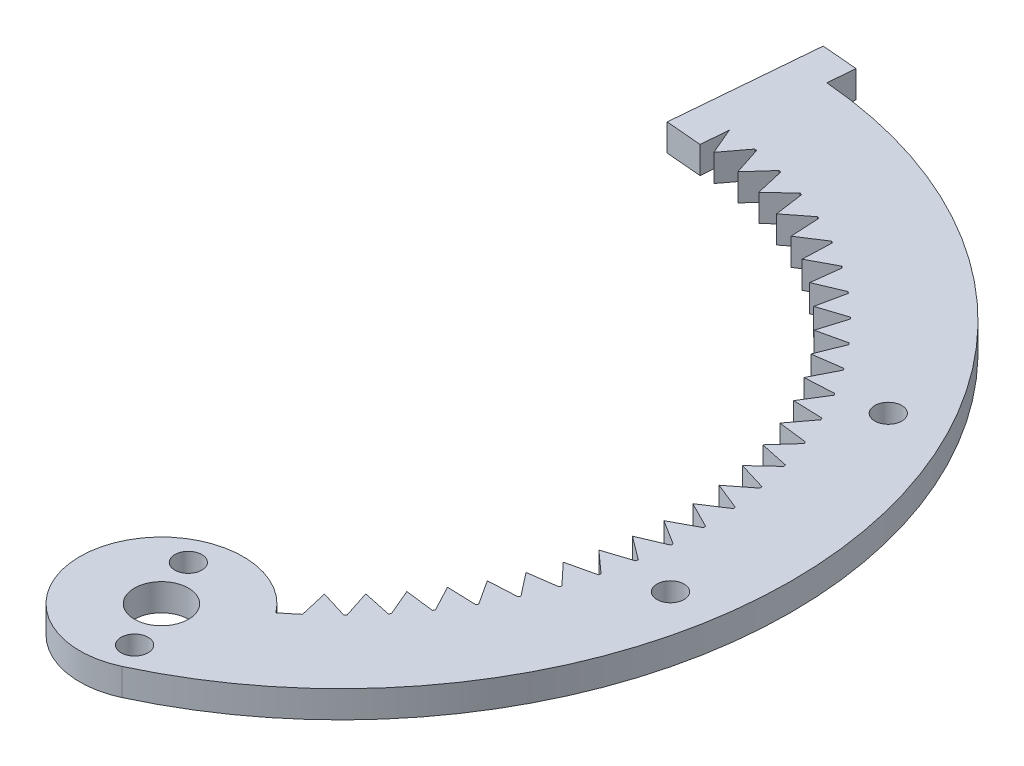
SolidWorks part; units mm, degrees
ref_plane "前视基准面" through (0, 0, 0) normal (0, 0, 1) x (1, 0, 0)
ref_plane "上视基准面" through (0, 0, 0) normal (0, 1, 0) x (1, 0, 0)
ref_plane "右视基准面" through (0, 0, 0) normal (1, 0, 0) x (0, 0, -1)
sketch "草图1" plane through (0, 0, 0) normal (0, 1, 0) x (1, 0, 0)
  line L0 (-22.706, 22.2911) -> (-15.0307, 111.7093) construction
  line L1 (-1.2848, 20.4524) -> (-44.7839, 24.1861) construction
  line L54 (-14.2519, 74.0104) -> (-13.9954, 76.9994)
  line L55 (-14.2519, 74.0104) -> (-18.2373, 74.3525)
  line L56 (-18.2373, 74.3525) -> (-16.8689, 90.2939)
  line L57 (-16.8689, 90.2939) -> (-12.8836, 89.9518)
  line L58 (-17.5531, 82.3232) -> (-4.3646, 81.1911) construction
  line L59 (-13.9954, 76.9994) -> (-12.7263, 74.0133)
  line L60 (-12.7263, 74.0133) -> (-10.7748, 76.6054)
  line L62 (-9.529, 73.4797) -> (-7.359, 75.8918)
  line L63 (-10.533, 76.565) -> (-9.529, 73.4797)
  line L64 (-6.3903, 72.6694) -> (-4.0184, 74.8833)
  line L65 (-7.1216, 75.8305) -> (-6.3903, 72.6694)
  line L66 (-3.3342, 71.5887) -> (-0.7783, 73.5874)
  line L67 (-3.7872, 74.8015) -> (-3.3342, 71.5887)
  line L68 (-0.384, 70.2458) -> (2.3364, 72.0141)
  line L69 (-0.5552, 73.4858) -> (-0.384, 70.2458)
  line L70 (2.438, 68.6508) -> (5.3022, 70.1753)
  line L71 (2.5499, 71.8935) -> (2.438, 68.6508)
  line L72 (5.1103, 66.816) -> (8.0964, 68.085)
  line L73 (5.5043, 70.0365) -> (5.1103, 66.816)
  line L74 (7.6125, 64.7552) -> (10.6978, 65.7592)
  line L75 (8.2857, 67.9292) -> (7.6125, 64.7552)
  line L76 (9.9255, 62.4842) -> (13.0866, 63.2154)
  line L77 (10.8728, 65.5874) -> (9.9255, 62.4842)
  line L78 (12.0318, 60.0202) -> (15.2446, 60.4732)
  line L79 (13.2459, 63.0291) -> (12.0318, 60.0202)
  line L80 (13.9153, 57.382) -> (17.1554, 57.5533)
  line L81 (15.3871, 60.2736) -> (13.9153, 57.382)
  line L82 (15.5618, 54.5897) -> (18.8044, 54.4779)
  line L83 (17.2799, 57.3421) -> (15.5618, 54.5897)
  line L84 (16.9586, 51.6646) -> (20.1792, 51.2706)
  line L85 (18.9101, 54.2567) -> (16.9586, 51.6646)
  line L86 (18.0951, 48.6288) -> (21.2691, 47.9556)
  line L87 (20.2651, 51.041) -> (18.0951, 48.6288)
  line L88 (18.9628, 45.5055) -> (22.066, 44.5583)
  line L89 (21.3347, 47.7194) -> (18.9628, 45.5055)
  line L90 (19.5549, 42.3185) -> (22.5638, 41.1044)
  line L91 (22.1108, 44.3172) -> (19.5549, 42.3185)
  line L92 (19.867, 39.092) -> (22.7586, 37.6203)
  line L93 (22.5874, 40.8604) -> (19.867, 39.092)
  line L94 (19.8967, 35.8506) -> (22.649, 34.1325)
  line L95 (22.7608, 37.3751) -> (19.8967, 35.8506)
  line L96 (19.6438, 32.619) -> (22.2359, 30.6675)
  line L97 (22.6299, 33.888) -> (19.6438, 32.619)
  line L98 (19.1102, 29.4216) -> (21.5224, 27.2516)
  line L99 (22.1955, 30.4256) -> (19.1102, 29.4216)
  line L100 (18.3, 26.283) -> (20.5138, 23.911)
  line L101 (21.4611, 27.0142) -> (18.3, 26.283)
  line L102 (17.2193, 23.2269) -> (19.2179, 20.671)
  line L103 (20.4321, 23.6799) -> (17.2193, 23.2269)
  line L104 (15.8763, 20.2766) -> (17.6446, 17.5562)
  line L150 (-13.1402, 86.9628) -> (-12.8836, 89.9518)
  line L154 (19.1164, 20.4478) -> (15.8763, 20.2766)
  line L155 (14.2813, 17.4546) -> (15.8058, 14.5905)
  line L156 (17.524, 17.3428) -> (14.2813, 17.4546)
  line L157 (12.4465, 14.7824) -> (13.7155, 11.7963)
  line L158 (15.667, 14.3884) -> (12.4465, 14.7824)
  line L159 (10.3857, 12.2802) -> (11.3897, 9.1948)
  line L160 (13.5597, 11.607) -> (10.3857, 12.2802)
  line L161 (8.1147, 9.9672) -> (8.8459, 6.8061)
  line L162 (11.2179, 9.0199) -> (8.1147, 9.9672)
  line L163 (-17.2384, 37.1311) -> (-12.7263, 74.0133) construction
  line L164 (-17.2384, 37.1311) -> (-9.529, 73.4797) construction
  arc A26 (7.2187, 5.479) -> (8.8459, 6.8061) centre (-17.2384, 37.1311) ccw
  arc A27 (-10.533, 76.565) -> (-10.7748, 76.6054) centre (-17.2384, 37.1311) ccw
  arc A28 (-7.1216, 75.8305) -> (-7.359, 75.8918) centre (-17.2384, 37.1311) ccw
  arc A29 (-3.7872, 74.8015) -> (-4.0184, 74.8833) centre (-17.2384, 37.1311) ccw
  arc A30 (-0.5552, 73.4858) -> (-0.7783, 73.5874) centre (-17.2384, 37.1311) ccw
  arc A31 (2.5499, 71.8935) -> (2.3364, 72.0141) centre (-17.2384, 37.1311) ccw
  arc A32 (5.5043, 70.0365) -> (5.3022, 70.1753) centre (-17.2384, 37.1311) ccw
  arc A33 (8.2857, 67.9292) -> (8.0964, 68.085) centre (-17.2384, 37.1311) ccw
  arc A34 (10.8728, 65.5874) -> (10.6978, 65.7592) centre (-17.2384, 37.1311) ccw
  arc A35 (13.2459, 63.0291) -> (13.0866, 63.2154) centre (-17.2384, 37.1311) ccw
  arc A36 (15.3871, 60.2736) -> (15.2446, 60.4732) centre (-17.2384, 37.1311) ccw
  arc A37 (17.2799, 57.3421) -> (17.1554, 57.5533) centre (-17.2384, 37.1311) ccw
  arc A38 (18.9101, 54.2567) -> (18.8044, 54.4779) centre (-17.2384, 37.1311) ccw
  arc A39 (20.2651, 51.041) -> (20.1792, 51.2706) centre (-17.2384, 37.1311) ccw
  arc A40 (21.3347, 47.7194) -> (21.2691, 47.9556) centre (-17.2384, 37.1311) ccw
  arc A41 (22.1108, 44.3172) -> (22.066, 44.5583) centre (-17.2384, 37.1311) ccw
  arc A42 (22.5874, 40.8604) -> (22.5638, 41.1044) centre (-17.2384, 37.1311) ccw
  arc A64 (7.2187, 5.479) -> (3.8161, -8.2199) centre (0, 0) ccw
  circle A65 centre (0, 0) radius 3
  arc A66 (22.7608, 37.3751) -> (22.7586, 37.6203) centre (-17.2384, 37.1311) ccw
  arc A67 (22.6299, 33.888) -> (22.649, 34.1325) centre (-17.2384, 37.1311) ccw
  arc A70 (22.1955, 30.4256) -> (22.2359, 30.6675) centre (-17.2384, 37.1311) ccw
  arc A71 (21.4611, 27.0142) -> (21.5224, 27.2516) centre (-17.2384, 37.1311) ccw
  arc A72 (20.4321, 23.6799) -> (20.5138, 23.911) centre (-17.2384, 37.1311) ccw
  arc A73 (19.1164, 20.4478) -> (19.2179, 20.671) centre (-17.2384, 37.1311) ccw
  arc A74 (17.524, 17.3428) -> (17.6446, 17.5562) centre (-17.2384, 37.1311) ccw
  arc A75 (15.667, 14.3884) -> (15.8058, 14.5905) centre (-17.2384, 37.1311) ccw
  arc A76 (13.5597, 11.607) -> (13.7155, 11.7963) centre (-17.2384, 37.1311) ccw
  arc A77 (11.2179, 9.0199) -> (11.3897, 9.1948) centre (-17.2384, 37.1311) ccw
  arc A137 (3.8161, -8.2199) -> (-13.1402, 86.9628) centre (-17.2384, 37.1311) ccw
  dimension "D1" = 6
  dimension "D2" = 50
  dimension "D6" = 40
  dimension "D3" = 43.6591
  dimension "D4" = 4
  dimension "D5" = 16
  dimension "D7" = 60
  dimension "D8" = 5
  dimension "D9" = 37.1572
  dimension "D11" = 21.5
extrude "凸台-拉伸1" add sketch "草图1" along normal blind 3
sketch "草图2" plane through (0, 3, 0) normal (0, 1, 0) x (1, 0, 0)
  circle A2 centre (-2.4804, 5.4633) radius 1.5
  circle A3 centre (2.4804, -5.4633) radius 1.5
extrude "切除-拉伸1" cut sketch "草图2" against normal blind 35
sketch "草图3" plane through (0, 3, 0) normal (0, 1, 0) x (1, 0, 0)
  circle A0 centre (27.0951, 29.3841) radius 1.5
  circle A1 centre (22.0248, 58.6183) radius 1.5
  dimension "D1" = 3
extrude "切除-拉伸2" cut sketch "草图3" against normal blind 10
